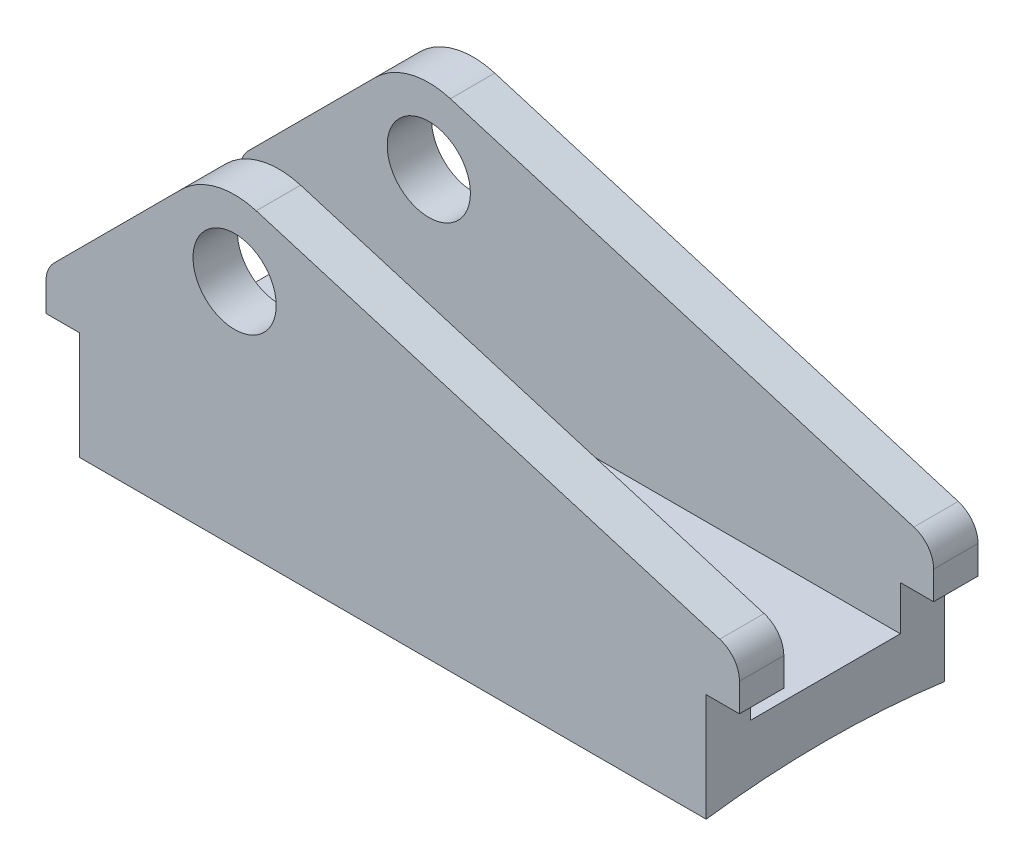
SolidWorks part; units mm, degrees
ref_plane "Front Plane" through (0, 0, 0) normal (0, 0, 1) x (1, 0, 0)
ref_plane "Top Plane" through (0, 0, 0) normal (0, 1, 0) x (1, 0, 0)
ref_plane "Right Plane" through (0, 0, 0) normal (1, 0, 0) x (0, 0, -1)
sketch "Sketch3" plane through (0, 0, 0) normal (0, 1, 0) x (1, 0, 0)
  line L1 (-56.5, -21.5) -> (56.5, -21.5)
  line L2 (-56.5, -21.5) -> (-56.5, 21.5)
  line L3 (-56.5, 21.5) -> (56.5, 21.5)
  line L4 (56.5, -21.5) -> (56.5, 21.5)
  line L5 (-56.5, -21.5) -> (56.5, 21.5) construction
  line L6 (-56.5, 21.5) -> (56.5, -21.5) construction
  point P0 (0, 0)
  dimension "D1" = 43
  dimension "D2" = 113
extrude "Boss-Extrude1" add sketch "Sketch3" along normal mid plane 20
sketch "Sketch4" plane through (56.5, 0, 0) normal (1, 0, 0) x (0, 0, -1)
  line L0 (-21.5, -10) -> (-21.5, 0) construction
  line L1 (-21.5, 10) -> (-21.5, -10) construction
  line L2 (-21.5, 0) -> (21.5, 0) construction
  line L3 (21.5, 10) -> (21.5, -10) construction
  line L4 (-21.5, 10) -> (21.5, 10) construction
  line L5 (-21.5, -10) -> (21.5, -10) construction
  line L6 (-21.5, 10) -> (-21.5, -10)
  line L7 (21.5, 10) -> (21.5, -10)
  line L8 (-21.5, -10) -> (21.5, -10)
  circle A0 centre (0, -160) radius 160
  line M3 (-21.5, -10) -> (21.5, -10)
  line M4 (21.5, -10) -> (21.5, 10)
  dimension "D2" = 320
  dimension "D1" = 10
sketch "Sketch5" plane through (0, 0, 21.5) normal (0, 0, 1) x (1, 0, 0)
  line L0 (56.5, 0) -> (-56.5, 0)
  line L1 (56.5, 10) -> (56.5, -10) construction
  line L2 (-56.5, 10) -> (-56.5, -10) construction
  line L3 (-56.5, 0) -> (-56.5, 18)
  line L4 (-56.5, 18) -> (-62.5, 18)
  line L5 (-62.5, 18) -> (-62.5, 23.0915)
  line L6 (-61.0355, 26.6271) -> (-38.0813, 49.5813)
  line L7 (56.5, 0) -> (56.5, 18)
  line L8 (56.5, 18) -> (62.5, 18)
  line L9 (62.5, 18) -> (62.5, 23.0915)
  line L10 (58.9386, 27.8801) -> (-24.6015, 52.9771)
  line L11 (-28.5, 40) -> (-28.5, 58.4244) construction
  line L12 (-28.5, 58.4244) -> (-53.5456, 58.4244) construction
  arc A0 (-38.0813, 49.5813) -> (-24.6015, 52.9771) centre (-28.5, 40) cw
  arc A1 (-61.0355, 26.6271) -> (-62.5, 23.0915) centre (-57.5, 23.0915) ccw
  circle A2 centre (-28.5, 40) radius 7.5
  arc A3 (62.5, 23.0915) -> (58.9386, 27.8801) centre (57.5, 23.0915) ccw
  point P17 (-28.5, 53.55)
  dimension "D1" = 5
  dimension "D3" = 18
  dimension "D4" = 15
  dimension "D8" = 5
  dimension "D2" = 6
  dimension "D5" = 40
  dimension "D6" = 34
  dimension "D7" = 45
  dimension "D9" = 53.55
extrude "Boss-Extrude3" add sketch "Sketch5" against normal blind 8
mirror "Mirror1" about plane through (0, 0, 0) normal (0, 0, 1) of "Boss-Extrude3"
extrude "Cut-Extrude5" cut sketch "Sketch4" against normal through all contours L6 A0 M4 M3 | A0 L6 M4 M3
